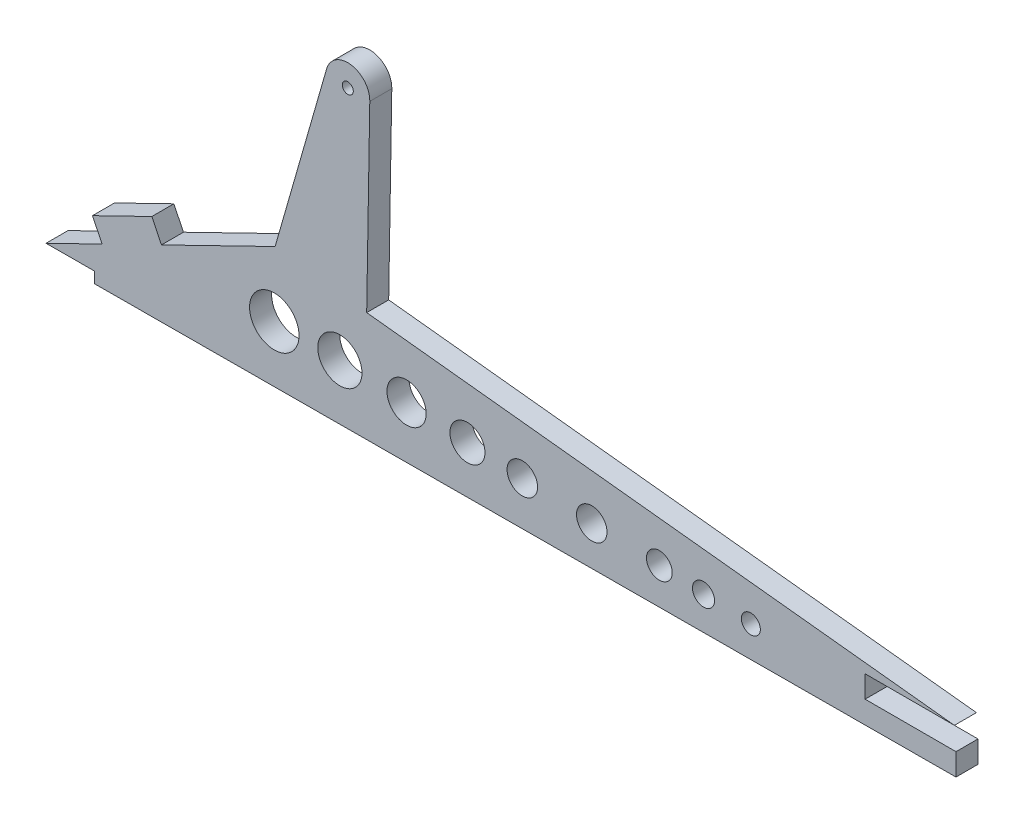
SolidWorks part; units mm, degrees
ref_plane "前视基准面" through (0, 0, 0) normal (0, 0, 1) x (1, 0, 0)
ref_plane "上视基准面" through (0, 0, 0) normal (0, 1, 0) x (1, 0, 0)
ref_plane "右视基准面" through (0, 0, 0) normal (1, 0, 0) x (0, 0, -1)
sketch "Model" plane through (0, 0, 0) normal (0, 0, 1) x (1, 0, 0)
  line L0 (7.0381, 6.2878) -> (6.1613, 8.0854)
  line L1 (6.1613, 8.0854) -> (11.5541, 10.7156)
  line L2 (11.5541, 10.7156) -> (12.4308, 8.918)
  line L3 (7.0381, 6.2878) -> (1.9393, 3.801)
  line L4 (12.4308, 8.918) -> (22.7538, 13.9529)
  line L5 (6.368, 2.819) -> (39.0801, 2.9522)
  line L6 (39.0801, 2.9522) -> (84.6132, 3.1386)
  line L7 (1.9393, 3.801) -> (6.364, 3.819)
  line L8 (6.368, 2.819) -> (6.364, 3.819)
  line L9 (22.7538, 13.9529) -> (27.4299, 30.2596)
  line L10 (31.356, 29.6736) -> (31.0739, 12.9133)
  line L11 (31.0739, 12.9133) -> (84.4694, 7.1386)
  line L12 (76.357, 5.1386) -> (84.6132, 5.1386)
  line L13 (76.357, 7.1386) -> (84.4694, 7.1386)
  line L14 (76.357, 5.1386) -> (76.357, 7.1386)
  line L15 (84.6132, 3.1386) -> (84.6132, 5.1386)
  circle A0 centre (29.3567, 29.7233) radius 0.5
  arc A1 (31.356, 29.6736) -> (27.4299, 30.2596) centre (29.3567, 29.7233) ccw
  circle A2 centre (34.6976, 7.6545) radius 1.783
  circle A3 centre (40.2282, 7.2652) radius 1.5906
  circle A4 centre (57.6624, 6.323) radius 1.1683
  circle A5 centre (61.6776, 6.0497) radius 1.006
  circle A6 centre (65.9754, 5.8705) radius 0.8624
  circle A7 centre (45.2143, 6.9441) radius 1.3868
  circle A8 centre (28.6362, 7.9435) radius 2.0077
  circle A9 centre (22.6801, 8.0227) radius 2.2462
  circle A10 centre (51.5238, 6.5569) radius 1.3868
  point P33 (0, 0)
  point P39 (31.3561, 29.6782)
extrude "凸台-拉伸1" add sketch "Model" along normal blind 2
